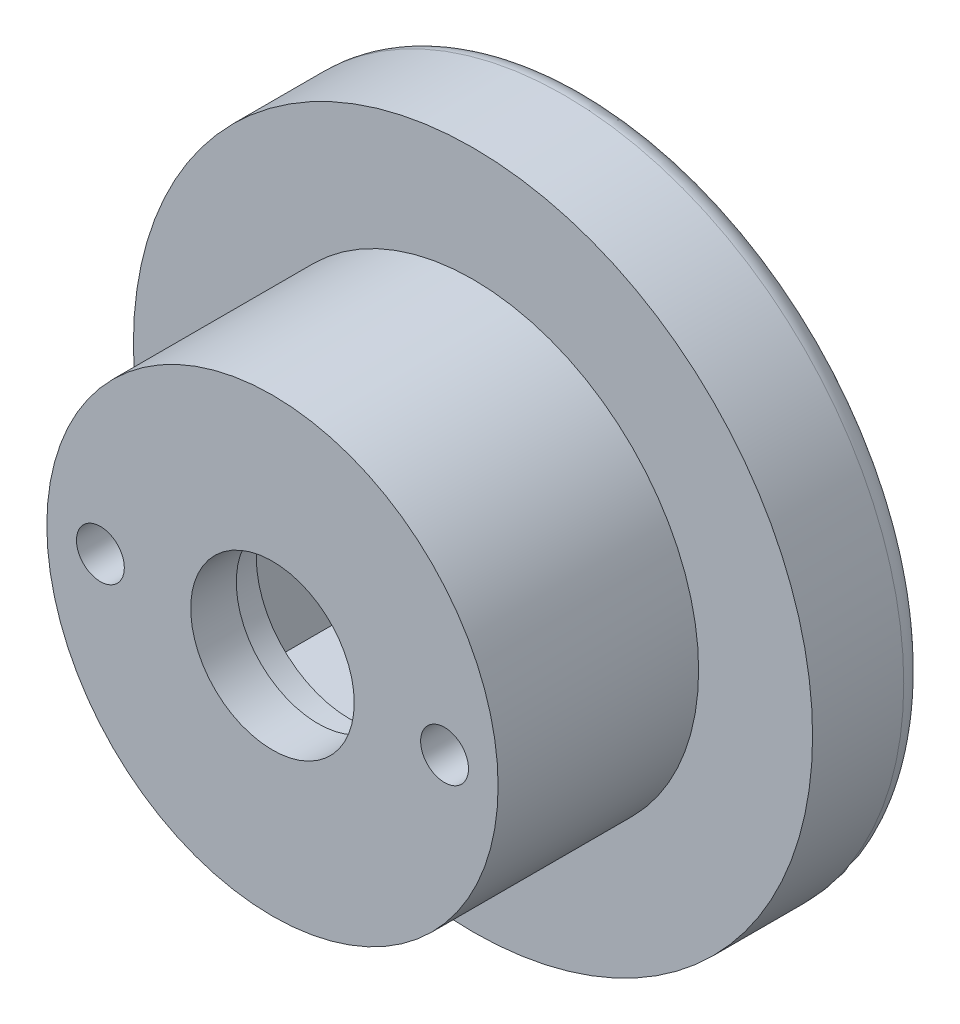
SolidWorks part; units mm, degrees
ref_plane "Front Plane" through (0, 0, 0) normal (0, 0, 1) x (1, 0, 0)
ref_plane "Top Plane" through (0, 0, 0) normal (0, 1, 0) x (1, 0, 0)
ref_plane "Right Plane" through (0, 0, 0) normal (1, 0, 0) x (0, 0, -1)
sketch "Sketch1" plane through (0, 0, 0) normal (0, 0, 1) x (1, 0, 0)
  circle A0 centre (0, 0) radius 4.0005 construction
  arc A1 (-0.3937, 3.9811) -> (0.3937, 3.9811) centre (0, 0) ccw construction
  circle A2 centre (0, 0) radius 4.1005
  circle A3 centre (0, 0) radius 10 construction
  circle A4 centre (0, 0) radius 10 construction
  circle A5 centre (0, 0) radius 9.9
  dimension "D1" = 0.1
  dimension "D2" = 0.1
extrude "Boss-Extrude1" add sketch "Sketch1" against normal up to surface (0.889 mm away)
sketch "Sketch2" plane through (0, 0, -0.889) normal (0, 0, -1) x (-1, 0, 0)
  line L0 (6.35, 6.5024) -> (6.35, 5.0927) construction
  line L1 (6.35, -6.5024) -> (-6.35, -6.5024) construction
  line L2 (6.35, -6.5024) -> (6.35, 6.5024) construction
  line L3 (6.35, 6.5024) -> (-6.35, 6.5024) construction
  line L4 (-6.35, -6.5024) -> (-6.35, 6.5024) construction
  line L6 (-6.22, 6.5024) -> (6.22, 6.5024) construction
  line L7 (6.22, -6.5024) -> (-6.22, -6.5024) construction
  line L8 (-6.35, -6.3724) -> (-6.35, -5.1435) construction
  line L9 (6.45, 6.6024) -> (-6.45, 6.6024)
  line L10 (-6.45, -6.6024) -> (-6.45, 6.6024)
  line L11 (6.45, -6.6024) -> (-6.45, -6.6024)
  line L12 (6.45, -6.6024) -> (6.45, 6.6024)
  circle A1 centre (0, 0) radius 9.9
  circle A2 centre (0, 0) radius 9.9
  dimension "D1" = 0
  dimension "D2" = 0.1
extrude "Boss-Extrude2" add sketch "Sketch2" along normal offset from surface (5.4086 mm away) 0.1
sketch "Sketch3" plane through (0, 0, -6.2976) normal (0, 0, -1) x (-1, 0, 0)
  line L4 (-6.45, -6.6024) -> (6.45, -6.6024)
  line L5 (6.45, -6.6024) -> (6.45, 6.6024)
  line L6 (6.45, 6.6024) -> (-6.45, 6.6024)
  line L7 (-6.45, 6.6024) -> (-6.45, -6.6024)
  line L8 (-6.45, -6.6024) -> (6.45, -6.6024)
  line L9 (6.45, -6.6024) -> (6.45, 6.6024)
  line L10 (6.45, 6.6024) -> (-6.45, 6.6024)
  line L11 (-6.45, 6.6024) -> (-6.45, -6.6024)
  circle A0 centre (0, 0) radius 14.9
  circle A1 centre (0, 0) radius 9.9
  circle A2 centre (0, 0) radius 9.9 construction
  dimension "D1" = 0
  dimension "D2" = 0
  dimension "D3" = 5
extrude "Boss-Extrude3" add sketch "Sketch3" along normal blind 5
sketch "Sketch4" plane through (0, 0, 0) normal (0, 0, 1) x (1, 0, 0)
  circle A0 centre (-7.5495, 0.0859) radius 1.05
  circle A1 centre (7.55, 0) radius 1.05
  circle A2 centre (7.55, 0) radius 1.05 construction
  circle A3 centre (-7.5495, 0.0859) radius 1.05 construction
extrude "Cut-Extrude6" cut sketch "Sketch4" against normal through all both and the other way through all
sketch "Sketch5" plane through (0, 0, 0) normal (0, 0, 1) x (1, 0, 0)
  circle A0 centre (0, 0) radius 4.1005 construction
  circle A1 centre (0, 0) radius 9.9
  circle A2 centre (0, 0) radius 9.9
  circle A3 centre (0, 0) radius 4.1005
  dimension "D1" = 0
extrude "Boss-Extrude4" add sketch "Sketch5" along normal blind 0.5
sketch "Sketch6" plane through (0, 0, 0.5) normal (0, 0, 1) x (1, 0, 0)
  line L0 (0.3937, 3.1505) -> (0.3937, 3.9811) construction
  circle A0 centre (0, 0) radius 3.5875
  circle A1 centre (0, 0) radius 9.9
  circle A2 centre (0, 0) radius 9.9 construction
  point P3 (0.3937, 3.5658)
extrude "Boss-Extrude5" add sketch "Sketch6" along normal blind 2
fillet "Fillet1" radius 1 1 edges at (-14.9, 0, -11.2976)
sketch "Sketch7" plane through (0, 0, 2.5) normal (0, 0, 1) x (1, 0, 0)
  circle A0 centre (7.55, 0) radius 1.05
  circle A1 centre (-7.5495, 0.0859) radius 1.05
  circle A2 centre (-7.5495, 0.0859) radius 1.05 construction
  circle A3 centre (7.55, 0) radius 1.05 construction
extrude "Cut-Extrude7" cut sketch "Sketch7" against normal through all both and the other way through all
